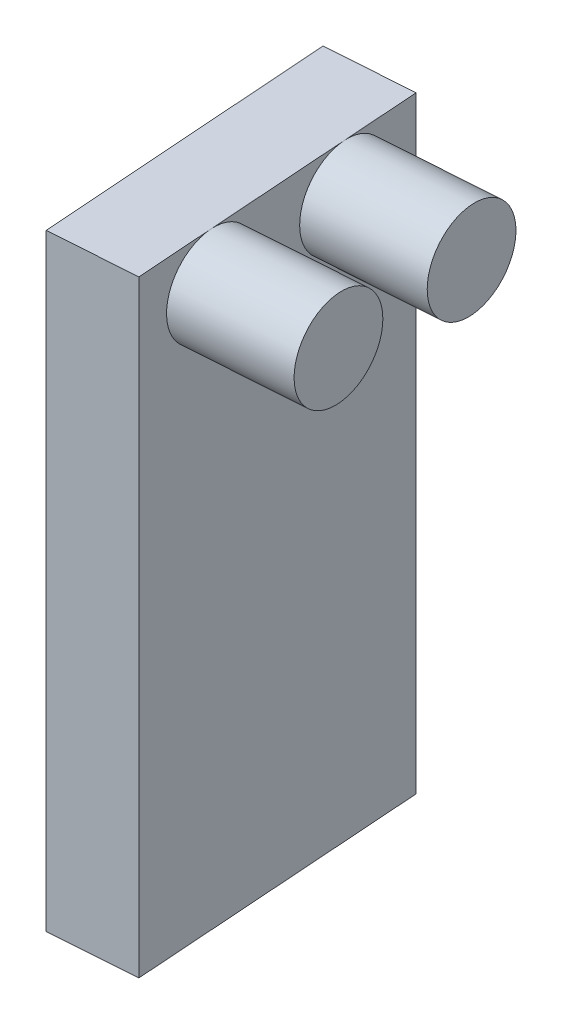
SolidWorks part; units mm, degrees
ref_plane "Front Plane" through (0, 0, 0) normal (0, 0, 1) x (1, 0, 0)
ref_plane "Top Plane" through (0, 0, 0) normal (0, 1, 0) x (1, 0, 0)
ref_plane "Right Plane" through (0, 0, 0) normal (1, 0, 0) x (0, 0, -1)
sketch "Sketch1" plane through (0, 0, 0) normal (0, 1, 0) x (1, 0, 0)
  line L0 (28.4005, -42.1195) -> (-28.4005, 42.1195)
  line L1 (-28.4005, 42.1195) -> (-6.1242, 87.7748)
  line L11 (-6.1242, 87.7748) -> (95.2294, 94.8464)
  line L12 (79.0773, -38.5837) -> (123.6299, 52.7269)
  line L13 (123.6299, 52.7269) -> (95.2294, 94.8464)
  line L14 (79.0773, -38.5837) -> (28.4005, -42.1195)
  line L15 (83.1766, -44.6631) -> (25.1852, -48.7093)
  line L16 (25.1852, -48.7093) -> (-35.7151, 41.6091)
  line L17 (-35.7151, 41.6091) -> (-10.2235, 93.8542)
  line L18 (-10.2235, 93.8542) -> (98.4447, 101.4362)
  line L19 (130.9445, 53.2373) -> (98.4447, 101.4362)
  line L20 (83.1766, -44.6631) -> (130.9445, 53.2373)
  point P4 (0, 0)
  dimension "D1" = 101.6
  dimension "D2" = 6.35
  dimension "D3" = 120
  dimension "D5" = 50.8
  dimension "D6" = 101.6
extrude "Boss-Extrude1" add sketch "Sketch1" along normal blind 25.4
sketch "Sketch2" plane through (0, 25.4, 0) normal (0, 1, 0) x (1, 0, 0)
  line L0 (123.1938, 58.9769) -> (124.0638, 46.5073)
  line L1 (130.5419, 59.4896) -> (131.412, 47.02)
  line L15 (123.1938, 58.9769) -> (130.5419, 59.4896)
  line L16 (131.412, 47.02) -> (124.0638, 46.5073)
  point P4 (123.6299, 52.7269)
  point P7 (123.6299, 52.7269)
  point P10 (123.6299, 52.7269)
  dimension "D1" = 12.5
extrude "Boss-Extrude2" add sketch "Sketch2" against normal up to surface (25.4 mm away) up to face at (48.6354, 0, -32.7941)
sketch "Sketch3" plane through (134.0401, 0, -9.3522) normal (0.9976, 0, -0.0696) x (-0.0696, 0, -0.9976)
  circle A0 centre (41.0093, 23.4) radius 2
  circle A1 centre (47.0093, 23.4) radius 2
  point P3 (44.0093, 25.4)
extrude "Boss-Extrude3" add sketch "Sketch3" along normal blind 5 contours A0 | A1
sketch "Sketch4" plane through (0, 25.4, 0) normal (0, 1, 0) x (1, 0, 0)
  line L0 (126.8999, 59.2355) -> (127.7875, 46.7671)
ref_plane "Plane1" through (130.4555, 0, -9.2862) normal (0.9975, 0, -0.071) x (-0.071, 0, -0.9975)
other "SurfaceCut1"
